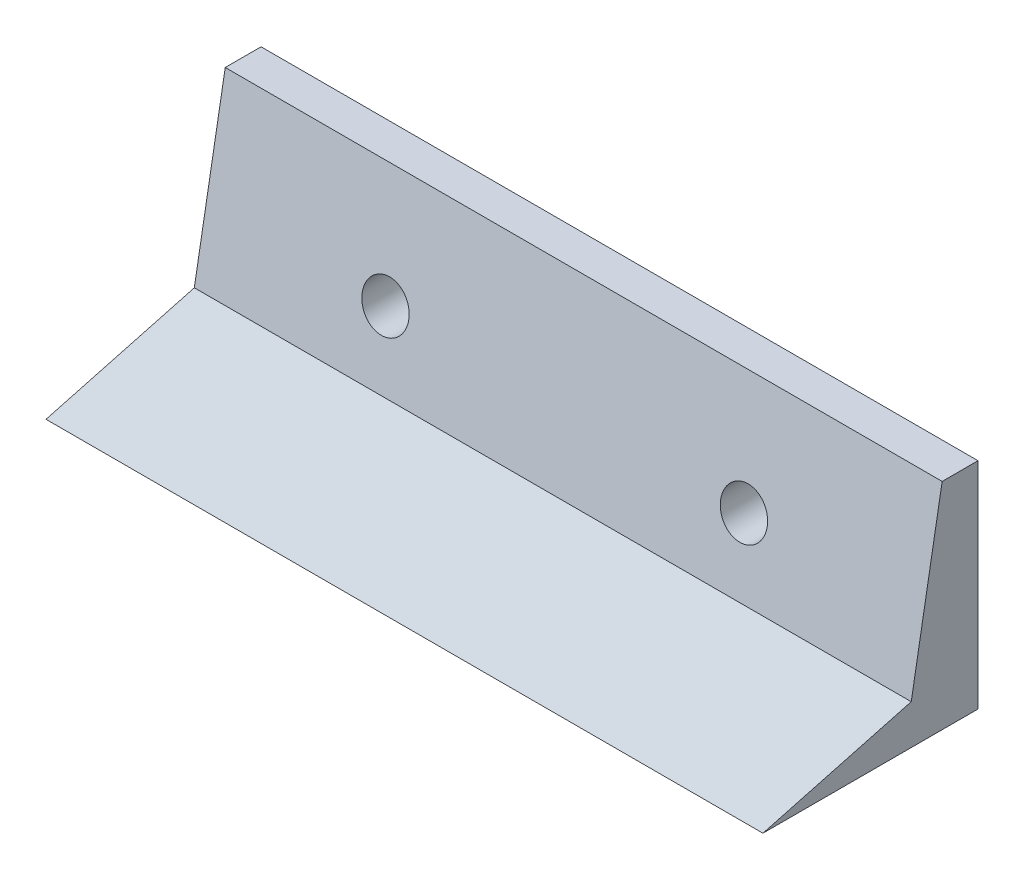
SolidWorks part; units mm, degrees
ref_plane "Front Plane" through (0, 0, 0) normal (0, 0, 1) x (1, 0, 0)
ref_plane "Top Plane" through (0, 0, 0) normal (0, 1, 0) x (1, 0, 0)
ref_plane "Right Plane" through (0, 0, 0) normal (1, 0, 0) x (0, 0, -1)
sketch "Sketch1" plane through (0, 0, 0) normal (1, 0, 0) x (0, 0, -1)
  line L0 (0, 0) -> (0, 30)
  line L3 (-30, 0) -> (0, 0)
  line L4 (-30, 0) -> (-9.3124, 5.5432)
  line L5 (-9.3124, 5.5432) -> (-5, 30)
  line L6 (-5, 30) -> (0, 30)
  dimension "D1" = 30
  dimension "D2" = 30
  dimension "D3" = 10
  dimension "D4" = 15
  dimension "D5" = 5
extrude "Boss-Extrude1" add sketch "Sketch1" along normal blind 100
sketch "Sketch2" plane through (0, 0, 0) normal (0, 0, -1) x (-1, 0, 0)
  line L0 (-100, 15) -> (0, 15) construction
  line L1 (-100, 0) -> (-100, 30) construction
  line L2 (0, 0) -> (0, 30) construction
  line L3 (-100, 30) -> (0, 30) construction
  point P8 (-75, 15)
  point P9 (-25, 15)
  dimension "D1" = 15
  dimension "D2" = 25
  dimension "D3" = 25
hole_wizard "M3 Clearance Hole1" positions "Sketch2" profile "Sketch3" hole size "M3" standard "ANSI Metric" end condition through all
sketch "Sketch3" plane through (25, 15, 0) normal (1, 0, 0) x (0, 1, 0)
  line L0 (0, 0) -> (0, 30)
  line L1 (0, 30) -> (1.7, 30)
  line L2 (1.7, 30) -> (1.7, 0)
  line L5 (1.7, 0) -> (0, 0)
  line L11 (0, -6.35) -> (0, 107.95) construction
  dimension "Thru Hole Dia." = 3.4
  dimension "Thru Hole Depth" = 30
ref_plane "Plane1" through (0, 0, 2.5) normal (0, 0, -1) x (-1, 0, 0)
sketch "Sketch4" plane through (0, 0, 2.5) normal (0, 0, -1) x (-1, 0, 0)
  circle A0 centre (-75, 15) radius 3.25
  circle A1 centre (-25, 15) radius 3.25
  dimension "D1" = 6.5
extrude "Cut-Extrude1" cut sketch "Sketch4" against normal through all
